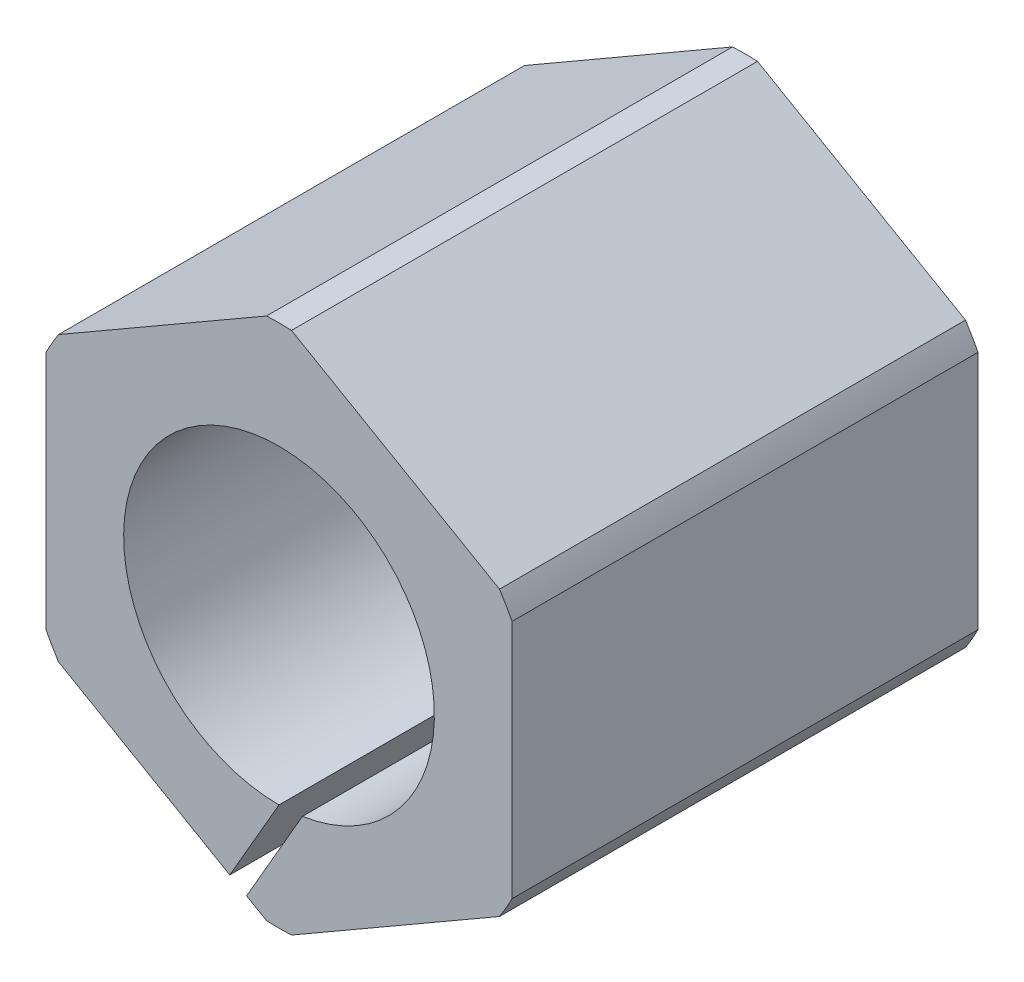
SolidWorks part; units mm, degrees
ref_plane "Front Plane" through (0, 0, 0) normal (0, 0, 1) x (1, 0, 0)
ref_plane "Top Plane" through (0, 0, 0) normal (0, 1, 0) x (1, 0, 0)
ref_plane "Right Plane" through (0, 0, 0) normal (1, 0, 0) x (0, 0, -1)
sketch "Sketch1" plane through (0, 0, 0) normal (0, 0, 1) x (1, 0, 0)
  line L1 (0, 10.9985) -> (-9.525, 5.4993)
  line L2 (-9.525, 5.4993) -> (-9.525, -5.4993)
  line L3 (-9.525, -5.4993) -> (0, -10.9985)
  line L4 (0, -10.9985) -> (9.525, -5.4993)
  line L5 (9.525, -5.4993) -> (9.525, 5.4993)
  line L6 (9.525, 5.4993) -> (0, 10.9985)
  circle A1 centre (0, 0) radius 6.35
  circle A2 centre (0, 0) radius 9.525 construction
  dimension "D1" = 12.7
  dimension "D3" = 19.05
extrude "Extrude1" add sketch "Sketch1" along normal mid plane 19.05
sketch "Sketch2" plane through (0, 0, 9.525) normal (0, 0, 1) x (1, 0, 0)
  circle A0 centre (0, 0) radius 10.7156
  dimension "D1" = 21.4312
extrude "Extrude2" cut sketch "Sketch2" against normal through all flip side to cut
sketch "Sketch3" plane through (0, 0, 9.525) normal (0, 0, 1) x (1, 0, 0)
  line L1 (3.437, -1.9844) -> (-1.3255, -10.2333)
  line L2 (3.437, -1.9844) -> (2.7496, -1.5875)
  line L3 (-1.3255, -10.2333) -> (-2.0129, -9.8364)
  line L4 (2.7496, -1.5875) -> (-2.0129, -9.8364)
  line L5 (-9.0139, -5.7944) -> (-0.5111, -10.7034) construction
  dimension "D1" = 0.7937
  dimension "D2" = 3.175
extrude "Extrude3" cut sketch "Sketch3" against normal through all
